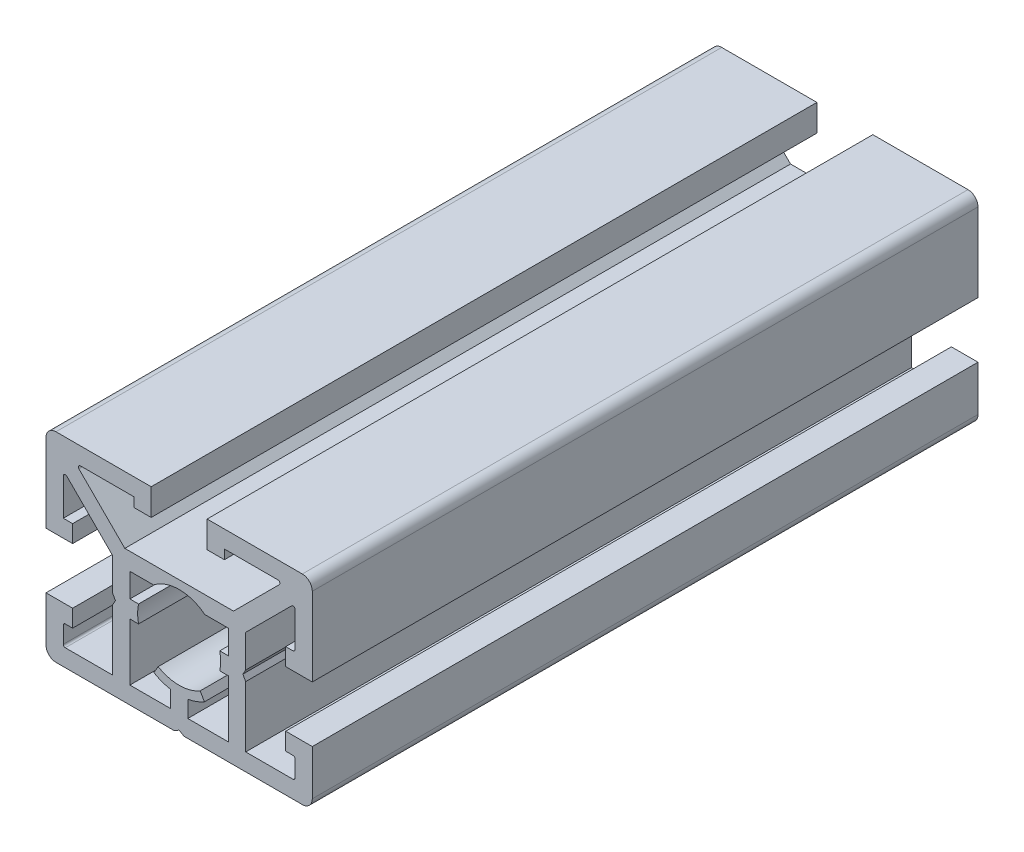
SolidWorks part; units mm, degrees
ref_plane "前视基准面" through (0, 0, 0) normal (0, 0, 1) x (1, 0, 0)
ref_plane "上视基准面" through (0, 0, 0) normal (0, 1, 0) x (1, 0, 0)
ref_plane "右视基准面" through (0, 0, 0) normal (1, 0, 0) x (0, 0, -1)
sketch "草图1" plane through (0, 0, 0) normal (0, 0, 1) x (1, 0, 0)
  line L0 (-17.4688, -13.9402) -> (0.2812, -13.9402)
  line L1 (1.7812, -13.9402) -> (19.5312, -13.9402)
  line L2 (-7.1303, 6.0598) -> (9.1927, 6.0598)
  line L3 (-6.3688, 3.4598) -> (-2.8275, 3.4598)
  line L4 (4.89, 3.4598) -> (8.4312, 3.4598)
  line L9 (21.0312, -12.4402) -> (21.0312, -5.6402)
  line L10 (21.0312, 2.7598) -> (21.0312, 14.5598)
  line L11 (19.5312, 16.0598) -> (5.2312, 16.0598)
  line L12 (-3.1688, 16.0598) -> (-17.4688, 16.0598)
  line L13 (-18.9688, 14.5598) -> (-18.9688, 2.7598)
  line L14 (-18.9688, -5.6402) -> (-18.9688, -12.4402)
  line L15 (-14.9688, -8.2402) -> (-16.0688, -8.2402)
  line L16 (-16.3688, -8.5402) -> (-16.3688, -11.0402)
  line L17 (-16.0688, -11.3402) -> (-8.9688, -11.3402)
  line L18 (-6.3688, -11.3402) -> (-0.2688, -11.3402)
  line L19 (2.3312, -11.3402) -> (8.4312, -11.3402)
  line L20 (11.0312, -11.3402) -> (18.1312, -11.3402)
  line L21 (18.4312, -11.0402) -> (18.4312, -8.5402)
  line L22 (18.1312, -8.2402) -> (17.0312, -8.2402)
  line L23 (17.0312, 5.3598) -> (18.1312, 5.3598)
  line L24 (18.4312, 5.6598) -> (18.4312, 10.8971)
  line L25 (17.9191, 11.1092) -> (11.0312, 4.2213)
  line L26 (9.1927, 6.0598) -> (16.0806, 12.9477)
  line L27 (15.8685, 13.4598) -> (7.8312, 13.4598)
  line L28 (-5.7688, 13.4598) -> (-13.806, 13.4598)
  line L29 (-14.0182, 12.9477) -> (-7.1303, 6.0598)
  line L30 (-8.9688, 4.2213) -> (-15.8567, 11.1092)
  line L31 (-16.3688, 10.8971) -> (-16.3688, 5.3598)
  line L33 (-3.1688, 16.0598) -> (-3.1688, 12.0598)
  line L34 (-5.7688, 13.4598) -> (-5.7688, 12.0598)
  line L35 (11.0312, -11.3402) -> (11.0312, -2.1902)
  line L36 (11.0312, -0.6902) -> (11.0312, 4.2213)
  line L37 (8.4312, -11.3402) -> (8.4312, -2.7402)
  line L38 (8.4312, -0.1402) -> (8.4312, 3.4598)
  line L39 (-8.9688, -11.3402) -> (-8.9688, -2.1902)
  line L40 (-8.9688, -0.6902) -> (-8.9688, 4.2213)
  line L41 (-6.3688, -11.3402) -> (-6.3688, -2.7402)
  line L42 (-6.3688, -0.1402) -> (-6.3688, 3.4598)
  line L43 (-5.7688, 12.0598) -> (-3.1688, 12.0598)
  line L44 (5.2312, 16.0598) -> (5.2312, 12.0598)
  line L45 (7.8312, 13.4598) -> (7.8312, 12.0598)
  line L46 (7.8312, 12.0598) -> (5.2312, 12.0598)
  line L47 (21.0312, 2.7598) -> (17.0312, 2.7598)
  line L48 (17.0312, 5.3598) -> (17.0312, 2.7598)
  line L49 (21.0312, -5.6402) -> (17.0312, -5.6402)
  line L50 (17.0312, -8.2402) -> (17.0312, -5.6402)
  line L51 (-18.9688, 2.7598) -> (-14.9688, 2.7598)
  line L52 (-16.3688, 5.3598) -> (-14.9688, 5.3598)
  line L53 (-14.9688, 5.3598) -> (-14.9688, 2.7598)
  line L54 (-18.9688, -5.6402) -> (-14.9688, -5.6402)
  line L55 (-14.9688, -8.2402) -> (-14.9688, -5.6402)
  line L56 (-6.3688, -2.7402) -> (-5.0688, -2.7402)
  line L57 (7.1312, -2.7402) -> (8.4312, -2.7402)
  line L58 (-6.3688, -0.1402) -> (-5.0688, -0.1402)
  line L59 (7.1312, -0.1402) -> (8.4312, -0.1402)
  line L60 (2.3312, -11.3402) -> (2.3312, -8.8402)
  line L61 (-0.2688, -11.3402) -> (-0.2688, -8.8402)
  line L62 (-2.7688, -7.9217) -> (-2.1233, -6.8206)
  line L63 (4.1857, -6.8206) -> (4.8312, -7.9217)
  line L64 (1.0312, -13.5072) -> (0.2812, -13.9402)
  line L65 (1.7812, -13.9402) -> (1.0312, -13.5072)
  line L66 (-8.5358, -1.4402) -> (-8.9688, -0.6902)
  line L67 (-8.9688, -2.1902) -> (-8.5358, -1.4402)
  line L68 (10.5982, -1.4402) -> (11.0312, -0.6902)
  line L69 (11.0312, -2.1902) -> (10.5982, -1.4402)
  arc A0 (19.5312, -13.9402) -> (21.0312, -12.4402) centre (19.5312, -12.4402) ccw
  arc A1 (21.0312, 14.5598) -> (19.5312, 16.0598) centre (19.5312, 14.5598) ccw
  arc A2 (-17.4688, 16.0598) -> (-18.9688, 14.5598) centre (-17.4688, 14.5598) ccw
  arc A3 (-18.9688, -12.4402) -> (-17.4688, -13.9402) centre (-17.4688, -12.4402) ccw
  arc A4 (-16.0688, -8.2402) -> (-16.3688, -8.5402) centre (-16.0688, -8.5402) ccw
  arc A5 (-16.3688, -11.0402) -> (-16.0688, -11.3402) centre (-16.0688, -11.0402) ccw
  arc A6 (18.1312, -11.3402) -> (18.4312, -11.0402) centre (18.1312, -11.0402) ccw
  arc A7 (18.4312, -8.5402) -> (18.1312, -8.2402) centre (18.1312, -8.5402) ccw
  arc A8 (18.1312, 5.3598) -> (18.4312, 5.6598) centre (18.1312, 5.6598) ccw
  arc A9 (18.4312, 10.8971) -> (17.9191, 11.1092) centre (18.1312, 10.8971) ccw
  arc A10 (16.0806, 12.9477) -> (15.8685, 13.4598) centre (15.8685, 13.1598) ccw
  arc A11 (-13.806, 13.4598) -> (-14.0182, 12.9477) centre (-13.806, 13.1598) ccw
  arc A12 (-15.8567, 11.1092) -> (-16.3688, 10.8971) centre (-16.0688, 10.8971) ccw
  arc A13 (-2.1233, -6.8206) -> (4.1857, -6.8206) centre (1.0312, -1.4402) ccw
  arc A14 (4.89, 3.4598) -> (-2.8275, 3.4598) centre (1.0312, -1.4402) ccw
  arc A15 (2.3312, -8.8402) -> (4.8312, -7.9217) centre (1.0312, -1.4402) ccw
  arc A16 (-2.7688, -7.9217) -> (-0.2688, -8.8402) centre (1.0312, -1.4402) ccw
  arc A17 (-5.0688, -0.1402) -> (-5.0688, -2.7402) centre (1.0312, -1.4402) ccw
  arc A18 (7.1312, -2.7402) -> (7.1312, -0.1402) centre (1.0312, -1.4402) ccw
extrude "凸台-拉伸1" add sketch "草图1" along normal blind 100
